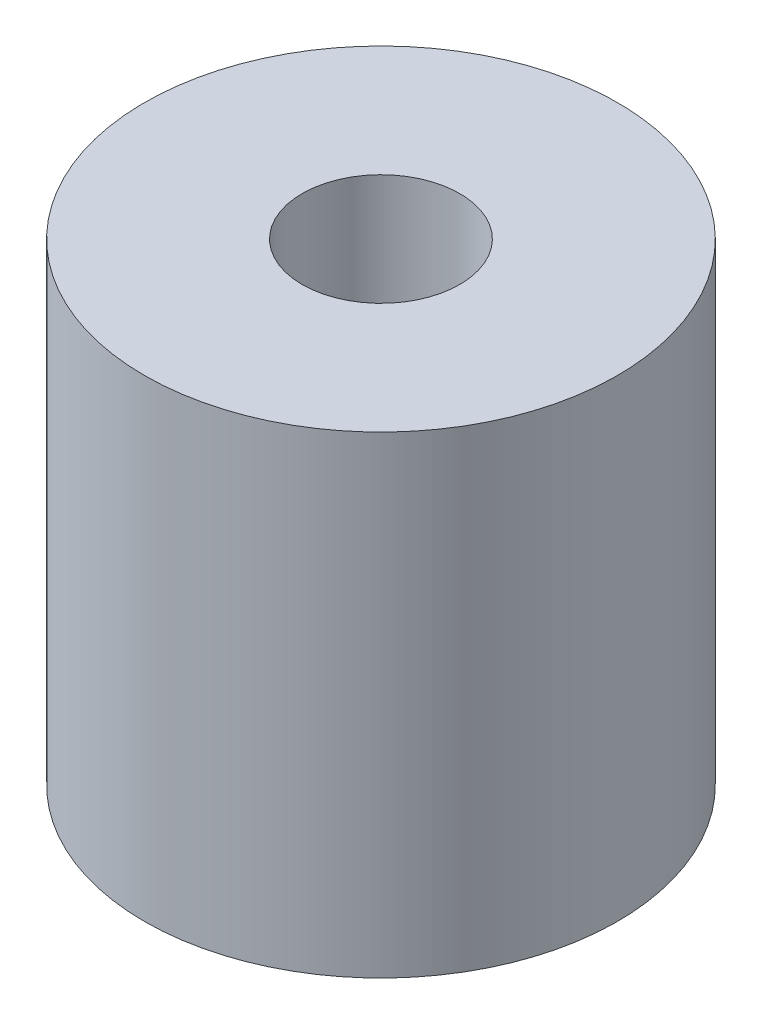
SolidWorks part; units mm, degrees
ref_plane "Front Plane" through (0, 0, 0) normal (0, 0, 1) x (1, 0, 0)
ref_plane "Top Plane" through (0, 0, 0) normal (0, 1, 0) x (1, 0, 0)
ref_plane "Right Plane" through (0, 0, 0) normal (1, 0, 0) x (0, 0, -1)
sketch "Sketch1" plane through (0, 0, 0) normal (0, 1, 0) x (1, 0, 0)
  circle A0 centre (0, 0) radius 1.5
  circle A1 centre (0, 0) radius 4.5
  dimension "D1" = 9
  dimension "D2" = 3
extrude "Boss-Extrude1" add sketch "Sketch1" along normal blind 9 contours A0
